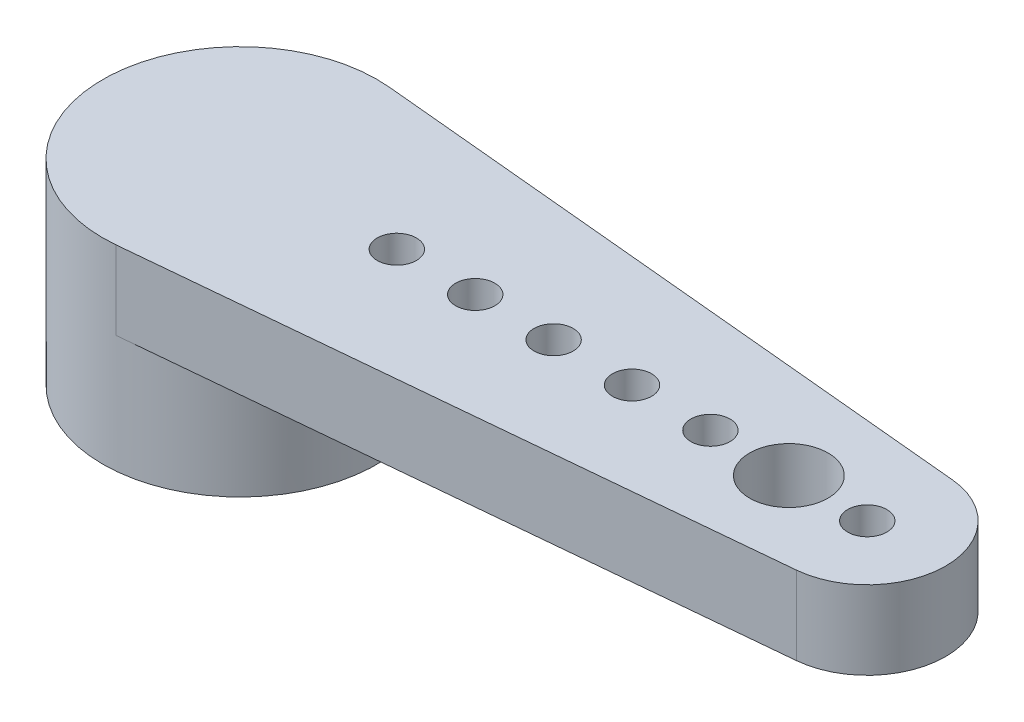
SolidWorks part; units mm, degrees
material "ABS"
ref_plane "Front Plane" through (0, 0, 0) normal (0, 0, 1) x (1, 0, 0)
ref_plane "Top Plane" through (0, 0, 0) normal (0, 1, 0) x (1, 0, 0)
ref_plane "Right Plane" through (0, 0, 0) normal (1, 0, 0) x (0, 0, -1)
sketch "Sketch1" plane through (0, 0, 0) normal (0, 1, 0) x (1, 0, 0)
  circle A0 centre (0, 0) radius 3.5
  circle A1 centre (0, 0) radius 2.4
  dimension "D1" = 7
  dimension "D2" = 4.8
extrude "Boss-Extrude1" add sketch "Sketch1" along normal blind 3
sketch "Sketch2" plane through (0, 3, 0) normal (0, 1, 0) x (1, 0, 0)
  line L0 (0.3281, 3.4846) -> (16.1875, 1.9912)
  line L1 (0.3281, -3.4846) -> (16.1875, -1.9912)
  line L2 (12, 0) -> (10, 0) construction
  circle A0 centre (16, 0) radius 2
  circle A1 centre (0, 0) radius 3.5 construction
  circle A2 centre (0, 0) radius 3.5
  circle A3 centre (16, 0) radius 0.5
  circle A4 centre (14, 0) radius 1
  circle A5 centre (12, 0) radius 0.5
  circle A6 centre (10, 0) radius 0.5
  circle A7 centre (8, 0) radius 0.5
  circle A8 centre (6, 0) radius 0.5
  circle A9 centre (4, 0) radius 0.5
  dimension "D1" = 4
  dimension "D2" = 16
  dimension "D3" = 1
  dimension "D4" = 2
  dimension "D6" = 1
  dimension "D5" = 2
  dimension "D7" = 2
  dimension "D9" = 2
  dimension "D8" = 5
extrude "Boss-Extrude2" add sketch "Sketch2" along normal blind 2
